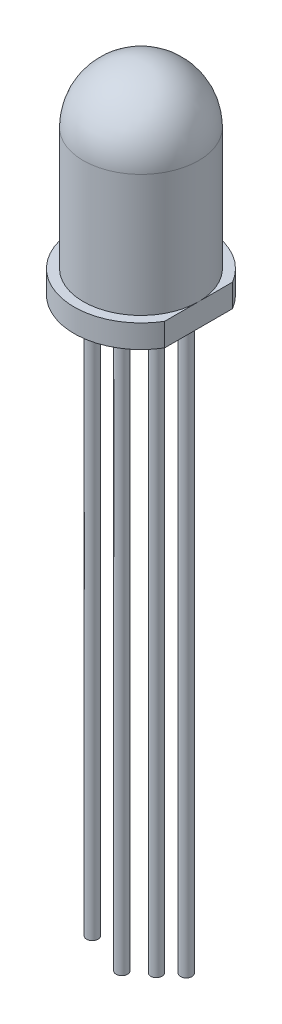
SolidWorks part; units mm, degrees
ref_plane "Front Plane" through (0, 0, 0) normal (0, 0, 1) x (1, 0, 0)
ref_plane "Top Plane" through (0, 0, 0) normal (0, 1, 0) x (1, 0, 0)
ref_plane "Right Plane" through (0, 0, 0) normal (1, 0, 0) x (0, 0, -1)
sketch "Sketch4" plane through (0, 0, 0) normal (0, 0, 1) x (1, 0, 0)
  line L0 (0, 2.5) -> (0, -6.3)
  line L1 (0, -6.3) -> (2.9, -6.3)
  line L2 (2.9, -6.3) -> (2.9, -5.3)
  line L3 (2.9, -5.3) -> (2.5, -5.3)
  line L4 (2.5, -5.3) -> (2.5, 0)
  arc A0 (2.5, 0) -> (0, 2.5) centre (0, 0) ccw
  dimension "D1" = 8.8
  dimension "D3" = 2.5
  dimension "D2" = 1
  dimension "D4" = 2.9
revolve "Revolve1" add sketch "Sketch4" angle 360 about L0
sketch "Sketch7" plane through (0, -6.3, 0) normal (0, -1, 0) x (-1, 0, 0)
  line L1 (-2.5, 1.4697) -> (-2.5, -1.4697)
  circle A2 centre (0, 0) radius 2.9 construction
  arc A3 (-2.5, 1.4697) -> (-2.5, -1.4697) centre (0, 0) ccw
  point P0 (0, 0)
extrude "Cut-Extrude1" cut sketch "Sketch7" against normal up to next
sketch "Sketch8" plane through (0, -6.3, 0) normal (0, -1, 0) x (-1, 0, 0)
  circle A0 centre (-1.966, 0) radius 0.25
  circle A1 centre (-0.6695, 0) radius 0.25
  circle A2 centre (0.8288, 0) radius 0.25
  circle A3 centre (2.1098, 0) radius 0.25
  point P8 (0, 0)
  point P9 (0, 0)
  point P10 (-1.966, 0)
  point P11 (2.1098, 0)
extrude "Boss-Extrude1" add sketch "Sketch8" along normal blind 26.5
sketch "Sketch9" plane through (0, 0, 0) normal (0, 0, 1) x (1, 0, 0)
  line L0 (2.216, -6.3) -> (2.216, -30.8017) construction
  line L1 (2.216, -32.8) -> (2.216, -6.3) construction
  line L2 (2.216, -30.8017) -> (1.716, -30.8017)
  line L3 (1.716, -6.3) -> (1.716, -32.8) construction
  line L4 (1.716, -30.8017) -> (0.9195, -31.4366)
  line L5 (0.9195, -32.8) -> (0.9195, -6.3) construction
  line L6 (0.9195, -31.4366) -> (0.4195, -31.4366)
  line L7 (0.4195, -6.3) -> (0.4195, -32.8) construction
  line L8 (0.4195, -31.4366) -> (-0.3182, -32.1126)
  line L9 (-0.3182, -32.1126) -> (-1.3426, -32.1126)
  line L10 (-1.3426, -32.1126) -> (-1.8598, -31.4366)
  line L11 (-1.8598, -32.8) -> (-1.8598, -6.3) construction
  line L12 (-1.8598, -31.4366) -> (-2.3598, -31.4366)
  line L13 (-2.3598, -6.3) -> (-2.3598, -32.8) construction
  line L14 (-2.3598, -31.4366) -> (-2.3598, -33.2656)
  line L15 (-2.3598, -33.2656) -> (2.6277, -33.2656)
  line L16 (2.6277, -33.2656) -> (2.6865, -30.8017)
  line L17 (2.6865, -30.8017) -> (2.216, -30.8017)
extrude "Cut-Extrude2" cut sketch "Sketch9" against normal through all and the other way through all
